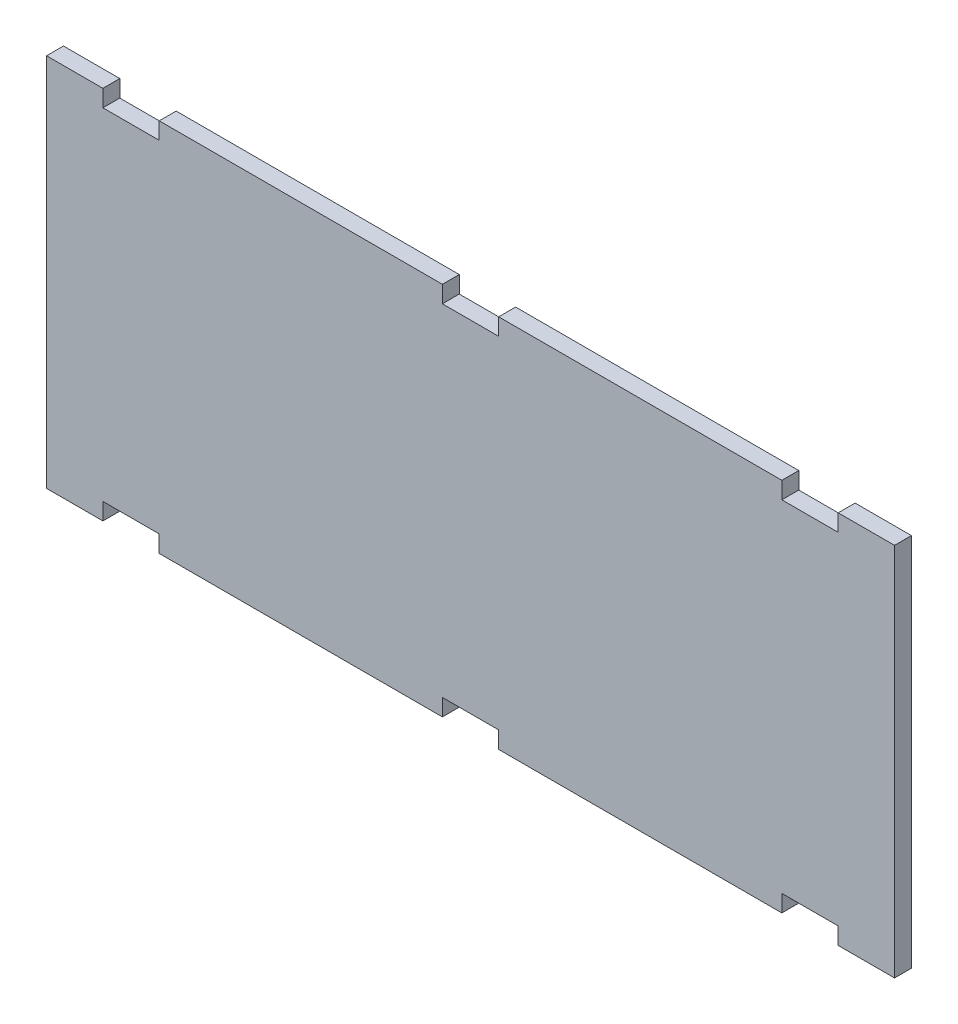
SolidWorks part; units mm, degrees
ref_plane "Plan de face" through (0, 0, 0) normal (0, 0, 1) x (1, 0, 0)
ref_plane "Plan de dessus" through (0, 0, 0) normal (0, 1, 0) x (1, 0, 0)
ref_plane "Plan de droite" through (0, 0, 0) normal (1, 0, 0) x (0, 0, -1)
sketch "Esquisse1" plane through (0, 0, 0) normal (0, 0, 1) x (1, 0, 0)
  line L0 (-301, 66.5) -> (0, 66.5) construction
  line L1 (-20, 0) -> (-20, 6)
  line L2 (0, 0) -> (0, 133)
  line L3 (0, 133) -> (-20, 133)
  line L4 (-301, 0) -> (-301, 133)
  line L5 (-301, 127) -> (0, 127) construction
  line L6 (-281, 133) -> (-301, 133)
  line L7 (-160.5, 133) -> (-261, 133)
  line L8 (-281, 133) -> (-281, 127)
  line L9 (-281, 127) -> (-261, 127)
  line L10 (-261, 133) -> (-261, 127)
  line L11 (-40, 133) -> (-140.5, 133)
  line L12 (-160.5, 133) -> (-160.5, 127)
  line L13 (-160.5, 127) -> (-140.5, 127)
  line L14 (-140.5, 133) -> (-140.5, 127)
  line L15 (-40, 6) -> (-20, 6)
  line L16 (-40, 133) -> (-40, 127)
  line L17 (-40, 127) -> (-20, 127)
  line L18 (-20, 133) -> (-20, 127)
  line L19 (0, 0) -> (-20, 0)
  line L20 (-140.5, 0) -> (-140.5, 6)
  line L21 (-160.5, 6) -> (-140.5, 6)
  line L22 (-40, 0) -> (-140.5, 0)
  line L23 (-261, 0) -> (-261, 6)
  line L24 (-281, 6) -> (-261, 6)
  line L25 (-281, 0) -> (-281, 6)
  line L26 (-160.5, 0) -> (-261, 0)
  line L27 (-281, 0) -> (-301, 0)
  line L28 (-160.5, 0) -> (-160.5, 6)
  line L29 (-40, 0) -> (-40, 6)
  dimension "D1" = 133
  dimension "D2" = 301
  dimension "D3" = 6
  dimension "D4" = 20
  dimension "D5" = 20
  dimension "D6" = 20
  dimension "D7" = 20
  dimension "D8" = 100.5
  dimension "D9" = 20
extrude "Boss.-Extru.1" add sketch "Esquisse1" along normal blind 6
